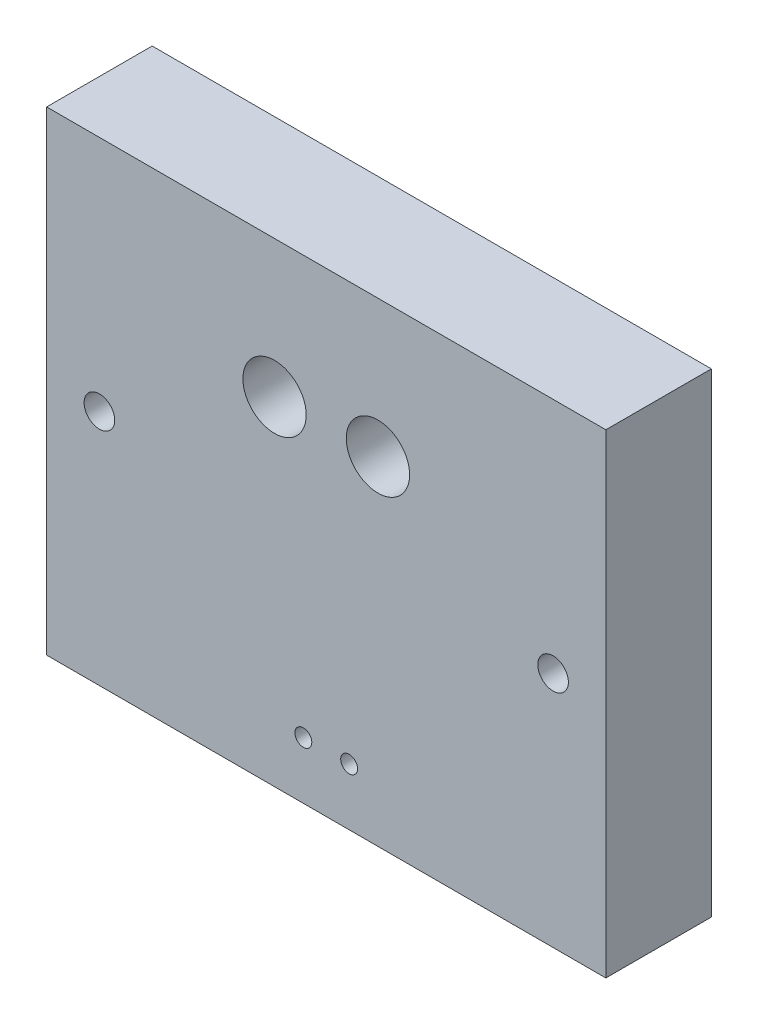
SolidWorks part; units mm, degrees
ref_plane "Alzado" through (0, 0, 0) normal (0, 0, 1) x (1, 0, 0)
ref_plane "Planta" through (0, 0, 0) normal (0, 1, 0) x (1, 0, 0)
ref_plane "Vista lateral" through (0, 0, 0) normal (1, 0, 0) x (0, 0, -1)
sketch "Croquis1" plane through (0, 0, 0) normal (0, 0, 1) x (1, 0, 0)
  line L1 (-18.0433, -25.2988) -> (34.9567, -25.2988)
  line L2 (-18.0433, -25.2988) -> (-18.0433, 19.7012)
  line L3 (-18.0433, 19.7012) -> (34.9567, 19.7012)
  line L4 (34.9567, -25.2988) -> (34.9567, 19.7012)
  dimension "D1" = 53
  dimension "D2" = 45
extrude "Saliente-Extruir1" add sketch "Croquis1" along normal blind 10
sketch "Croquis2" plane through (0, 0, 10) normal (0, 0, 1) x (1, 0, 0)
  line L1 (-18.0433, -25.2988) -> (34.9567, -25.2988) construction
  line L2 (-18.0433, -25.2988) -> (8.4567, -25.2988) construction
  line L3 (7.0867, -19.8988) -> (9.8267, -19.8988) construction
  circle A0 centre (6.2867, -19.8988) radius 0.8
  circle A1 centre (10.6267, -19.8988) radius 0.8
  point P4 (11.4267, -19.8988)
  point P7 (7.0867, -19.8988)
  point P8 (9.8267, -19.8988)
  point P9 (6.2867, -19.0988)
  point P10 (10.6267, -19.0988)
  point P16 (8.4567, -19.8988)
  dimension "D1" = 1.6
  dimension "D2" = 1.6
  dimension "D3" = 2.74
  dimension "D5" = 6.2
extrude "Cortar-Extruir1" cut sketch "Croquis2" against normal blind 10
sketch "Croquis3" plane through (0, 0, 10) normal (0, 0, 1) x (1, 0, 0)
  line L3 (34.9567, 19.7012) -> (-18.0433, 19.7012) construction
  line L5 (-18.0433, 19.7012) -> (-18.0433, -25.2988) construction
  circle A0 centre (13.3567, 6.7012) radius 1.45
  circle A1 centre (3.5567, 6.7012) radius 1.45
  point P4 (5.0067, 6.7012)
  point P5 (11.9067, 6.7012)
  point P8 (14.8067, 6.7012)
  dimension "D1" = 2.9
  dimension "D2" = 2.9
  dimension "D3" = 13
  dimension "D4" = 21.6
  dimension "D5" = 9.8
extrude "Cortar-Extruir2" cut sketch "Croquis3" against normal blind 10
sketch "Croquis4" plane through (0, 0, 10) normal (0, 0, 1) x (1, 0, 0)
  circle A0 centre (3.5567, 6.7012) radius 3
  circle A1 centre (13.3567, 6.7012) radius 3
  dimension "D1" = 6
  dimension "D2" = 6
extrude "Cortar-Extruir3" cut sketch "Croquis4" against normal blind 5
sketch "Croquis5" plane through (0, 0, 10) normal (0, 0, 1) x (1, 0, 0)
  line L0 (34.9567, 19.7012) -> (-18.0433, 19.7012) construction
  line L1 (-18.0433, 19.7012) -> (-18.0433, -25.2988) construction
  line L2 (8.4567, -25.2988) -> (8.4567, 19.7012) construction
  line L3 (-18.0433, -25.2988) -> (34.9567, -25.2988) construction
  circle A0 centre (-13.0433, -2.7988) radius 1.45
  circle A1 centre (29.9567, -2.7988) radius 1.45
  dimension "D1" = 2.9
  dimension "D2" = 22.5
  dimension "D3" = 5
extrude "Cortar-Extruir4" cut sketch "Croquis5" against normal blind 10
